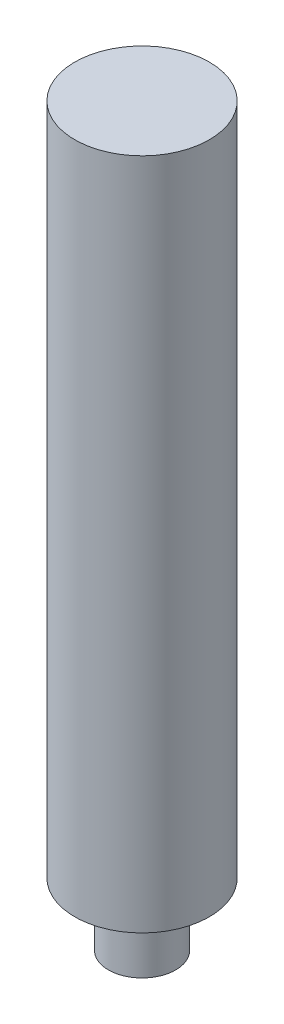
SolidWorks part; units mm, degrees
ref_plane "前基準面" through (0, 0, 0) normal (0, 0, 1) x (1, 0, 0)
ref_plane "上基準面" through (0, 0, 0) normal (0, 1, 0) x (1, 0, 0)
ref_plane "右基準面" through (0, 0, 0) normal (1, 0, 0) x (0, 0, -1)
sketch "草圖1" plane through (0, 0, 0) normal (0, 1, 0) x (1, 0, 0)
  circle A0 centre (0, 0) radius 1.5
extrude "填料-伸長1" add sketch "草圖1" along normal blind 2.8
sketch "草圖2" plane through (0, 2.8, 0) normal (0, 1, 0) x (1, 0, 0)
  circle A0 centre (0, 0) radius 3
extrude "填料-伸長2" add sketch "草圖2" along normal blind 30
